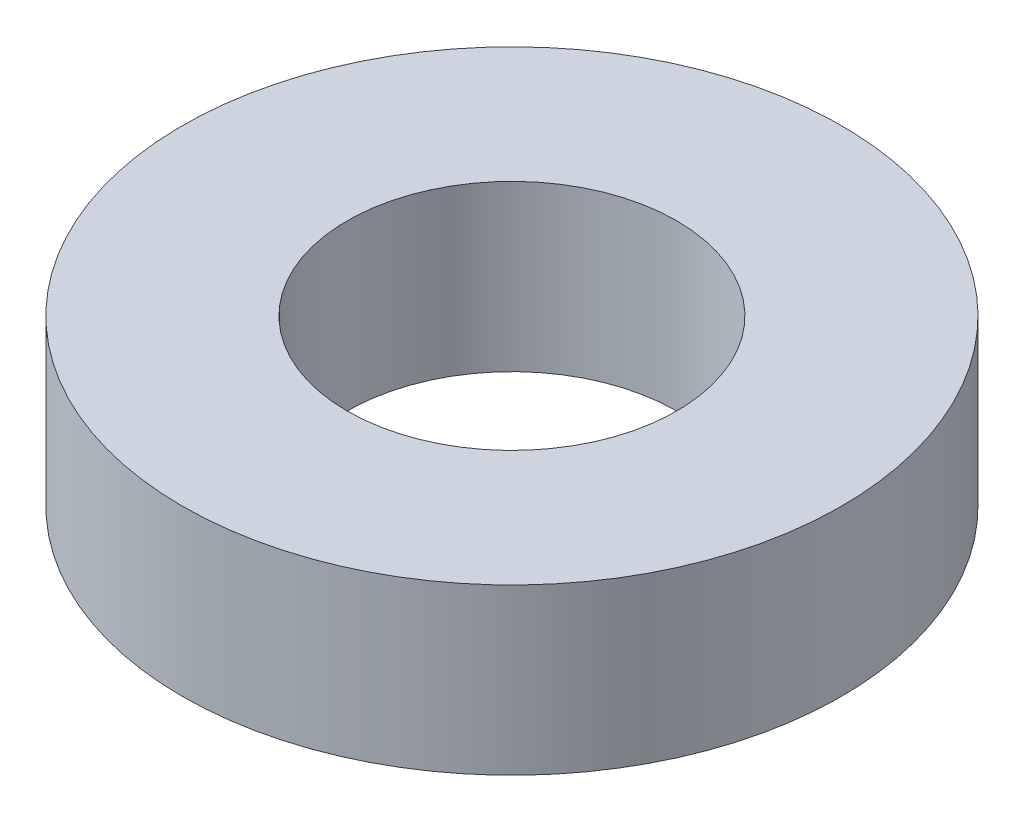
SolidWorks part; units mm, degrees
ref_plane "Front Plane" through (0, 0, 0) normal (0, 0, 1) x (1, 0, 0)
ref_plane "Top Plane" through (0, 0, 0) normal (0, 1, 0) x (1, 0, 0)
ref_plane "Right Plane" through (0, 0, 0) normal (1, 0, 0) x (0, 0, -1)
sketch "Sketch1" plane through (0, 0, 0) normal (0, 1, 0) x (1, 0, 0)
  circle A0 centre (0, 0) radius 6
  circle A1 centre (0, 0) radius 3
  dimension "D1" = 6
  dimension "D2" = 12
extrude "Boss-Extrude1" add sketch "Sketch1" along normal mid plane 3
